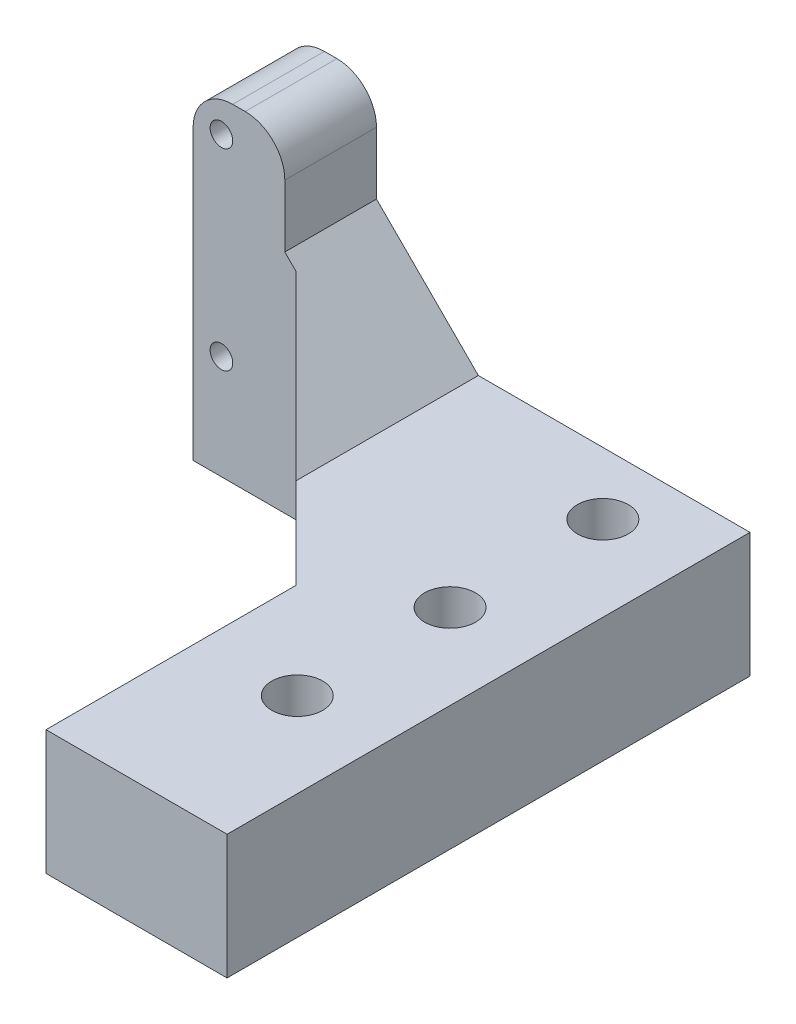
SolidWorks part; units mm, degrees
ref_plane "Plan de face" through (0, 0, 0) normal (0, 0, 1) x (1, 0, 0)
ref_plane "Plan de dessus" through (0, 0, 0) normal (0, 1, 0) x (1, 0, 0)
ref_plane "Plan de droite" through (0, 0, 0) normal (1, 0, 0) x (0, 0, -1)
sketch "Esquisse1" plane through (0, 0, 0) normal (0, 0, 1) x (1, 0, 0)
  line L1 (0, 0) -> (18, 0)
  line L2 (0, 0) -> (0, 29)
  line L3 (0, 29) -> (18, 29)
  line L4 (18, 0) -> (18, 29)
  dimension "D1" = 18
  dimension "D2" = 29
extrude "Boss.-Extru.1" add sketch "Esquisse1" along normal blind 46.2
sketch "Esquisse3" plane through (0, 0, 46.2) normal (0, 0, 1) x (1, 0, 0)
  line L0 (0, 29) -> (0, 0) construction
  line L3 (2.5, 9.2) -> (2.5, 26.2) construction
  line L4 (2.5, 26.2) -> (10.1767, 26.2) construction
  line L5 (0, 0) -> (18, 0) construction
  circle A2 centre (2.5, 26.2) radius 1
  circle A4 centre (2.5, 9.2) radius 1
  dimension "D1" = 2.5
  dimension "D5" = 17
  dimension "D3" = 2
  dimension "D2" = 9.2
extrude "Enlèv. mat.-Extru.1" cut sketch "Esquisse3" against normal through all
sketch "Esquisse4" plane through (0, 29, 0) normal (0, 1, 0) x (1, 0, 0)
  line L0 (0, -23.1) -> (18, -23.1) construction
  line L1 (0, -46.2) -> (0, 0) construction
  line L2 (18, -46.2) -> (18, 0) construction
  line L3 (0, -38.1) -> (0, -8.1)
  line L4 (0, -8.1) -> (18, -8.1)
  line L6 (18, -8.1) -> (18, -38.1)
  line L7 (18, 0) -> (0, 0) construction
  line L8 (0, -38.1) -> (18, -38.1)
  dimension "D1" = 8.1
extrude "Enlèv. mat.-Extru.2" cut sketch "Esquisse4" against normal through all
sketch "Esquisse5" plane through (0, 29, 0) normal (0, 1, 0) x (1, 0, 0)
  line L0 (18, 0) -> (0, 0) construction
  line L1 (18, -46.2) -> (26.1, -46.2)
  line L2 (18, -46.2) -> (18, 0)
  line L3 (18, 0) -> (26.1, 0)
  line L4 (26.1, -46.2) -> (26.1, 0)
  dimension "D1" = 8.1
extrude "Boss.-Extru.2" add sketch "Esquisse5" against normal up to vertex (29 mm away)
fillet "Congé1" radius 3.5 2 edges at (0, 29, 42.15) (0, 29, 4.05)
sketch "Esquisse7" plane through (0, 0, 0) normal (0, 0, -1) x (-1, 0, 0)
  line L1 (-26.1, 29) -> (-8.1, 29)
  line L2 (-26.1, 29) -> (-26.1, 11)
  line L3 (-26.1, 11) -> (-8.1, 11)
  line L4 (-8.1, 29) -> (-8.1, 11)
  dimension "D1" = 18
  dimension "D2" = 18
extrude "Enlèv. mat.-Extru.4" cut sketch "Esquisse7" against normal up to vertex
sketch "Esquisse8" plane through (0, 11, 0) normal (0, 1, 0) x (1, 0, 0)
  line L0 (26.1, 0) -> (8.1, 0) construction
  line L1 (26.1, -46.2) -> (41.1, -46.2)
  line L2 (26.1, -46.2) -> (26.1, 0)
  line L3 (26.1, 0) -> (41.1, 0)
  line L4 (41.1, -46.2) -> (41.1, 0)
  line L5 (33.6, -46.2) -> (33.6, 0) construction
  line L6 (33.6, -23.1) -> (26.1, -23.1) construction
  circle A0 centre (33.6, -5.5) radius 2.25
  circle A1 centre (33.6, -32.5) radius 2.25
  circle A2 centre (33.6, -19) radius 2.25
  dimension "D2" = 5.5
  dimension "D3" = 4.5
  dimension "D1" = 27
  dimension "D5" = 13.5
  dimension "D4" = 15
extrude "Boss.-Extru.3" add sketch "Esquisse8" against normal up to vertex (11 mm away) up to point (26.1, 0, 0)
chamfer "Chanfrein1" distance 9 angle 45 2 edges at (8.1, 11, 4.05) (8.1, 11, 42.15)
fillet "Congé2" radius 3.5 1 edges at (8.1, 29, 4.05)
sketch "Esquisse9" plane through (0, 11, 0) normal (0, 1, 0) x (1, 0, 0)
  line L0 (41.1, -46.2) -> (41.1, 0) construction
  line L1 (25.1, -46.2) -> (0, -46.2)
  line L2 (25.1, -46.2) -> (25.1, -8.1)
  line L3 (25.1, -8.1) -> (0, -8.1)
  line L4 (0, -46.2) -> (0, -8.1)
  line L5 (41.1, -46.2) -> (17.1, -46.2) construction
  point P5 (26.3568, -34.3312)
  point P9 (0, 0)
  point P10 (25.1, -46.2)
  point P13 (0, -8.1)
  dimension "D1" = 16
extrude "Enlèv. mat.-Extru.5" cut sketch "Esquisse9" against normal through all both and the other way through all
chamfer "Chanfrein2" distance 16 angle 45 1 edges at (25.1, 5.5, 8.1)
